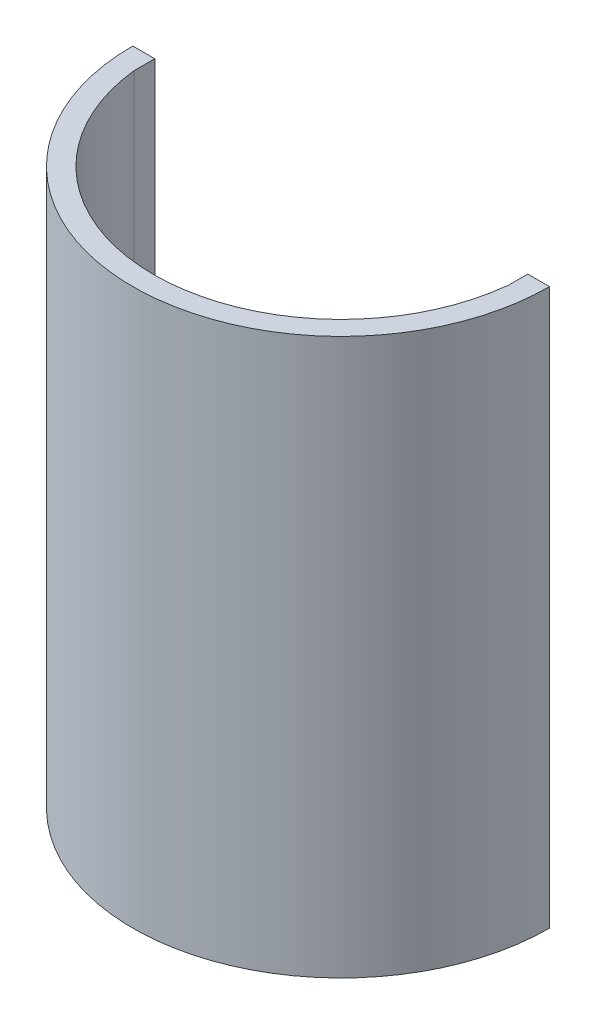
SolidWorks part; units mm, degrees
ref_plane "Front Plane" through (0, 0, 0) normal (0, 0, 1) x (1, 0, 0)
ref_plane "Top Plane" through (0, 0, 0) normal (0, 1, 0) x (1, 0, 0)
ref_plane "Right Plane" through (0, 0, 0) normal (1, 0, 0) x (0, 0, -1)
sketch "Sketch1" plane through (0, 0, 0) normal (0, 1, 0) x (1, 0, 0)
  line L0 (-76.2, 0) -> (76.2, 0)
  arc A0 (-76.2, 0) -> (76.2, 0) centre (0, 0) ccw
  dimension "D1" = 152.4
extrude "Boss-Extrude1" add sketch "Sketch1" along normal blind 203.2
sketch "Sketch2" plane through (0, 203.2, 0) normal (0, 1, 0) x (1, 0, 0)
  line L3 (68.1554, -7.62) -> (-68.1554, -7.62)
  line L4 (68.1554, -7.62) -> (-68.1554, -7.62)
  arc A3 (-68.1554, -7.62) -> (68.1554, -7.62) centre (0, 0) ccw
  arc A4 (-68.1554, -7.62) -> (68.1554, -7.62) centre (0, 0) ccw
  dimension "D1" = 7.62
extrude "Cut-Extrude1" cut sketch "Sketch2" against normal blind 203.2
sketch "Sketch3" plane through (0, 203.2, 0) normal (0, 1, 0) x (1, 0, 0)
  line L0 (76.2, 0) -> (-76.2, 0) construction
  line L1 (-68.1554, -7.62) -> (68.2658, -7.62)
  line L2 (-68.1554, -7.62) -> (-68.1554, 0)
  line L3 (-68.1554, 0) -> (68.2658, 0)
  line L4 (68.2658, -7.62) -> (68.2658, 0)
extrude "Cut-Extrude2" cut sketch "Sketch3" against normal blind 203.2
